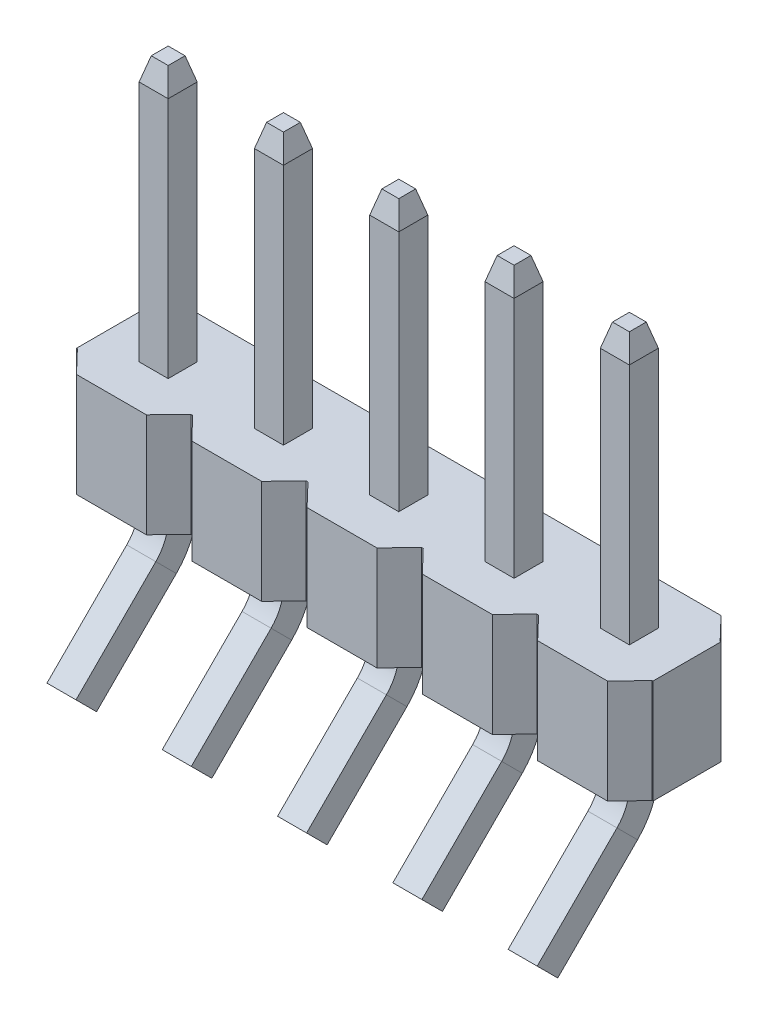
SolidWorks part; units mm, degrees
ref_plane "Front Plane" through (0, 0, 0) normal (0, 0, 1) x (1, 0, 0)
ref_plane "Top Plane" through (0, 0, 0) normal (0, 1, 0) x (1, 0, 0)
ref_plane "Right Plane" through (0, 0, 0) normal (1, 0, 0) x (0, 0, -1)
sketch "Sketch1" plane through (0, 0, 0) normal (0, 1, 0) x (1, 0, 0)
  line L14 (-0.77, 1.25) -> (0.77, 1.25)
  line L20 (-0.77, -1.25) -> (0.77, -1.25)
  line L22 (1.27, -0.75) -> (1.27, 0.75)
  line L23 (1.27, -1.25) -> (-1.27, 1.25) construction
  line L24 (0.77, -1.25) -> (1.25, -0.75)
  line L25 (1.25, -0.75) -> (1.27, -0.75)
  line L26 (0, 0) -> (0, -1.4708) construction
  line L27 (0, 0) -> (1.4893, 0) construction
  line L28 (0.77, 1.25) -> (1.25, 0.75)
  line L29 (1.25, 0.75) -> (1.27, 0.75)
  line L30 (-1.25, 0.75) -> (-1.27, 0.75)
  line L31 (-0.77, 1.25) -> (-1.25, 0.75)
  line L32 (-1.25, -0.75) -> (-1.27, -0.75)
  line L33 (-0.77, -1.25) -> (-1.25, -0.75)
  line L34 (-1.27, -0.75) -> (-1.27, 0.75)
  point P25 (0, 1.25)
  point P29 (0, 0)
  point P38 (1.27, 0)
  point P43 (0, -1.25)
  dimension "D11" = 1.25
  dimension "D12" = 1.27
  dimension "D13" = 0.5
  dimension "D14" = 0.02
  dimension "D15" = 0.5
extrude "Boss-Extrude1" add sketch "Sketch1" along normal blind 2.29
sketch "Sketch2" plane through (0, 0, 0) normal (1, 0, 0) x (0, 0, -1)
  line L0 (0, 8.13) -> (0, -0.4081)
  line L1 (-0.75, 2.29) -> (0.75, 2.29) construction
  line L2 (-0.3661, -1.292) -> (-2.1241, -3.05)
  line L3 (0.75, 0) -> (1.25, 0) construction
  arc A0 (0, -0.4081) -> (-0.3661, -1.292) centre (-1.25, -0.4081) cw
  dimension "D4" = 1.25
  dimension "D1" = 5.84
  dimension "D2" = 135
  dimension "D3" = 3.05
ref_plane "Plane1" through (0, 8.13, 0) normal (0, 1, 0) x (1, 0, 0)
sketch "Sketch3" plane through (0, 8.13, 0) normal (0, 1, 0) x (1, 0, 0)
  line L1 (-0.32, 0.32) -> (0.32, 0.32)
  line L2 (-0.32, 0.32) -> (-0.32, -0.32)
  line L3 (-0.32, -0.32) -> (0.32, -0.32)
  line L4 (0.32, 0.32) -> (0.32, -0.32)
  line L5 (-0.32, 0.32) -> (0.32, -0.32) construction
  line L6 (-0.32, -0.32) -> (0.32, 0.32) construction
  point P0 (0, 0)
  dimension "D1" = 0.64
sweep "Sweep1" add profiles "Sketch3" path "Sketch2"
chamfer "Chamfer3" distance 0.5 angle 15 4 edges at (0, 8.13, 0.32) (-0.32, 8.13, 0) (0, 8.13, -0.32) (0.32, 8.13, 0)
pattern_linear "LPattern1" count 5 spacing 2.54 along (1, 0, 0) of "Boss-Extrude1", "Sweep1", "Chamfer3"
